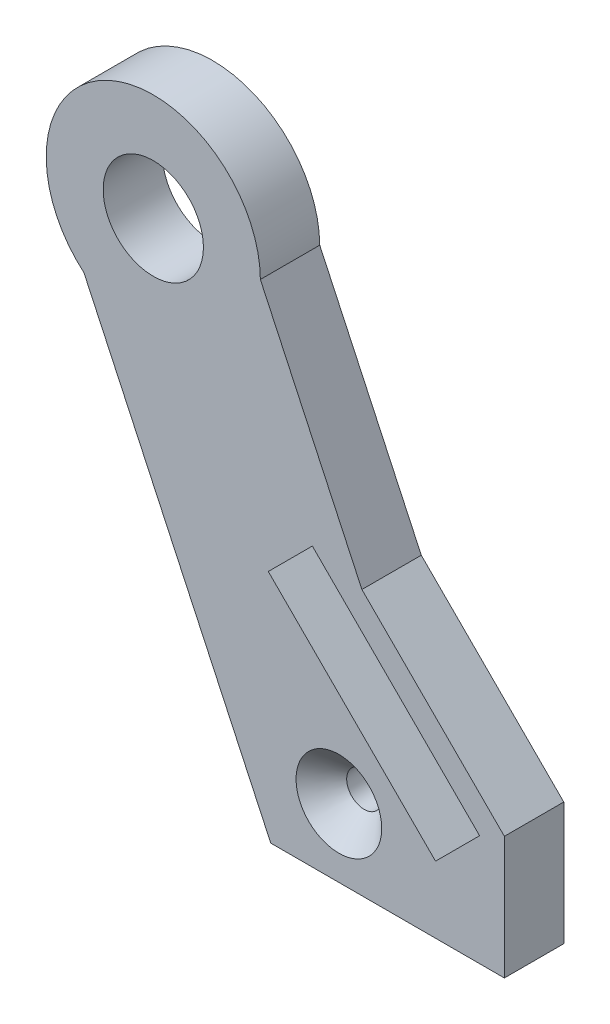
SolidWorks part; units mm, degrees
ref_plane "Front Plane" through (0, 0, 0) normal (0, 0, 1) x (1, 0, 0)
ref_plane "Top Plane" through (0, 0, 0) normal (0, 1, 0) x (1, 0, 0)
ref_plane "Right Plane" through (0, 0, 0) normal (1, 0, 0) x (0, 0, -1)
sketch "Sketch1" plane through (0, 0, 0) normal (0, 0, 1) x (1, 0, 0)
  line L0 (0, 12) -> (12, 0) construction
  line L1 (0, 0) -> (12, 0)
  line L2 (0, 0) -> (0, 12)
  line L3 (0, 12) -> (12, 12)
  line L4 (12, 0) -> (12, 12)
  line L5 (0, 0) -> (3.5, 0)
  line L6 (0, 0) -> (0, 3.5)
  line L7 (0, 3.5) -> (3.5, 3.5)
  line L8 (3.5, 0) -> (3.5, 3.5)
  line L9 (8.2662, 3.6278) -> (8.3192, 3.6808) construction
  line L10 (8.4645, 3.4295) -> (-0.1269, 12.0208)
  line L11 (-0.1269, 12.0208) -> (2.1359, 14.2836)
  line L12 (8.4645, 3.4295) -> (10.7272, 5.6922)
  line L13 (2.1359, 14.2836) -> (10.7272, 5.6922)
  line L14 (0, 0) -> (-10.5655, 22.6577)
  line L15 (-10.5655, 22.6577) -> (-1.5024, 26.8839)
  line L16 (-1.5024, 26.8839) -> (4.6816, 13.6223)
  line L17 (4.6816, 13.6223) -> (12, 6.3039)
  line L18 (12, 0) -> (8.5175, 3.4825)
  circle A0 centre (3.5, 3.5) radius 0.9
  circle A1 centre (-6.0339, 24.7708) radius 2.575
  circle A3 centre (-6.0339, 24.7708) radius 5.5
  dimension "D5" = 1.8
  dimension "D6" = 5.15
  dimension "D7" = 11
  dimension "D1" = 12
  dimension "D2" = 12
  dimension "D3" = 3.5
  dimension "D4" = 3.5
  dimension "D8" = 45
  dimension "D9" = 25
  dimension "D10" = 90
  dimension "D11" = 90
  dimension "D12" = 14.6325
  dimension "D13" = 10.3498
  dimension "D14" = 3.2
  dimension "D15" = 12.15
  dimension "D16" = 0.075
  dimension "D17" = 4.925
  dimension "D19" = 160
extrude "Boss-Extrude1" add sketch "Sketch1" along normal blind 3.05 contours L15 A3 A1 | L15 A3 A1 | A3 L14 L2 L10 L11 L13 L3 L17 L16 | L17 L3 L13 L12 L0 L4 | A0 L8 L1 L0 L2 L7 | A0 L7 L2 L1 L8
hole_wizard "CSK for M2 Flat Head Machine Screw1" positions "Sketch2" profile "Sketch3" countersink size "M2" standard "ANSI Metric" end condition through all
sketch "Sketch2" plane through (0, 0, 3.05) normal (0, 0, 1) x (1, 0, 0)
  point P0 (3.5, 3.5)
sketch "Sketch3" plane through (3.5, 3.5, 3.05) normal (1, 0, 0) x (0, -1, 0)
  line L0 (0, 0) -> (0, 3.05)
  line L1 (0, 3.05) -> (0.9, 3.05)
  line L2 (0.9, 3.05) -> (0.9, 1.3)
  line L3 (0.9, 1.3) -> (2.2, 0)
  line L5 (2.2, 0) -> (0, 0)
  line L6 (-0.9, 1.3) -> (-2.2, 0) construction
  line L11 (0, -6.35) -> (0, 107.95) construction
  dimension "Thru Hole Dia." = 1.8
  dimension "Thru Hole Depth" = 3.05
  dimension "Near C'Sink Dia." = 4.4
  dimension "Near C'Sink Angle" = 90
